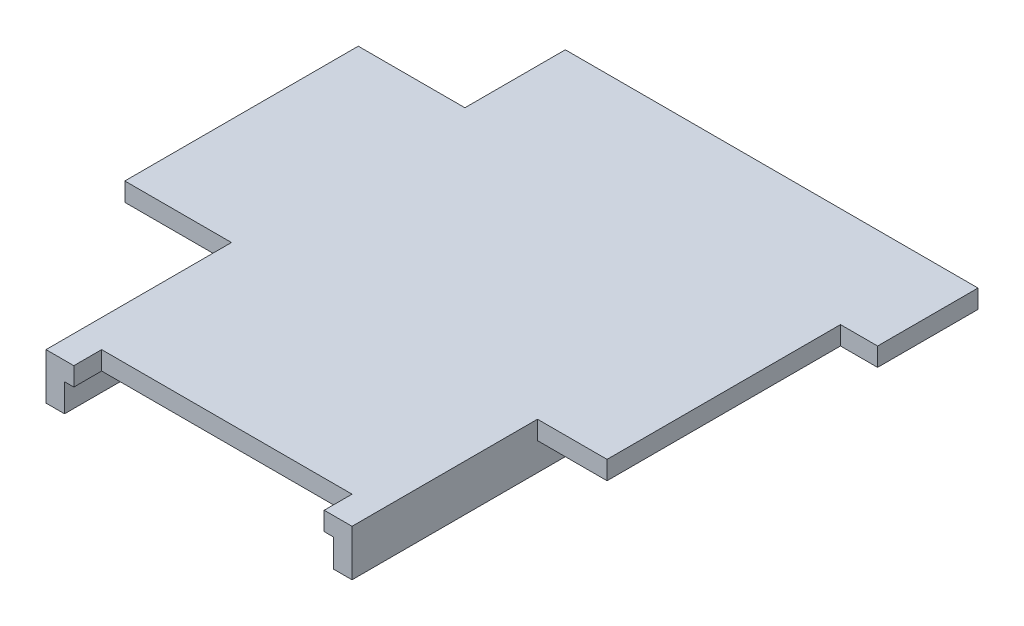
SolidWorks part; units mm, degrees
ref_plane "Alzado" through (0, 0, 0) normal (0, 0, 1) x (1, 0, 0)
ref_plane "Planta" through (0, 0, 0) normal (0, 1, 0) x (1, 0, 0)
ref_plane "Vista lateral" through (0, 0, 0) normal (1, 0, 0) x (0, 0, -1)
sketch "Croquis3" plane through (0, 0, 0) normal (0, 1, 0) x (1, 0, 0)
  line L12 (10.0641, 59.4125) -> (60.1359, 59.4125)
  line L13 (63.1, 48.5842) -> (63.1, 56.4484)
  line L14 (20.6, 3.4125) -> (49.6, 3.4125)
  line L15 (7.1, 56.4484) -> (7.1, 23.4125)
  line L16 (59.1, 48.5842) -> (59.1, 23.4125)
  line L18 (20.6, 3.4125) -> (20.6, 23.4125)
  line L19 (20.6, 23.4125) -> (7.1, 23.4125)
  line L22 (49.6, 3.4125) -> (49.6, 23.4125)
  line L23 (49.6, 23.4125) -> (59.1, 23.4125)
  line L25 (63.1, 48.5842) -> (59.1, 48.5842)
  line L29 (7.1, 56.4484) -> (7.1, 59.4125)
  line L30 (7.1, 59.4125) -> (10.0641, 59.4125)
  line L31 (60.1359, 59.4125) -> (63.1, 59.4125)
  line L32 (63.1, 59.4125) -> (63.1, 56.4484)
  dimension "D1" = 3.4125
  dimension "D2" = 7.1
  dimension "D13" = 56
  dimension "D14" = 56
  dimension "D15" = 20
  dimension "D16" = 20
extrude "Saliente-Extruir1" add sketch "Croquis3" along normal blind 2
sketch "Croquis4" plane through (20.6, 0, 0) normal (-1, 0, 0) x (0, 0, 1)
  line L1 (-3.4125, 2) -> (-56.4484, 2)
  line L2 (-3.4125, 2) -> (-3.4125, -3)
  line L3 (-3.4125, -3) -> (-56.4484, -3)
  line L4 (-56.4484, 2) -> (-56.4484, -3)
  dimension "D1" = 5
extrude "Saliente-Extruir2" add sketch "Croquis4" along normal blind 2
sketch "Croquis5" plane through (49.6, 0, 0) normal (1, 0, 0) x (0, 0, -1)
  line L1 (3.4125, 2) -> (56.4484, 2)
  line L2 (3.4125, 2) -> (3.4125, -3)
  line L3 (3.4125, -3) -> (56.4484, -3)
  line L4 (56.4484, 2) -> (56.4484, -3)
extrude "Saliente-Extruir3" add sketch "Croquis5" along normal blind 2
sketch "Croquis6" plane through (0, 2, 0) normal (0, 1, 0) x (1, 0, 0)
  line L0 (18.6, 3.4125) -> (18.6, 23.4125) construction
  line L1 (7.1, 59.4125) -> (18.6, 59.4125)
  line L2 (7.1, 59.4125) -> (7.1, 48.5842)
  line L3 (7.1, 48.5842) -> (18.6, 48.5842)
  line L4 (18.6, 59.4125) -> (18.6, 48.5842)
  line L5 (59.1, 48.5842) -> (63.1, 48.5842) construction
  line L6 (18.6, 3.4125) -> (51.6, 3.4125) construction
  line L7 (48.6, 3.4125) -> (21.6, 3.4125)
  line L8 (48.6, 3.4125) -> (48.6, 6.4125)
  line L9 (48.6, 6.4125) -> (21.6, 6.4125)
  line L10 (21.6, 3.4125) -> (21.6, 6.4125)
  line L11 (51.6, 23.4125) -> (51.6, 3.4125) construction
  dimension "D1" = 0
  dimension "D2" = 0
  dimension "D3" = 3
  dimension "D4" = 3
  dimension "D5" = 3
extrude "Cortar-Extruir1" cut sketch "Croquis6" against normal blind 10
